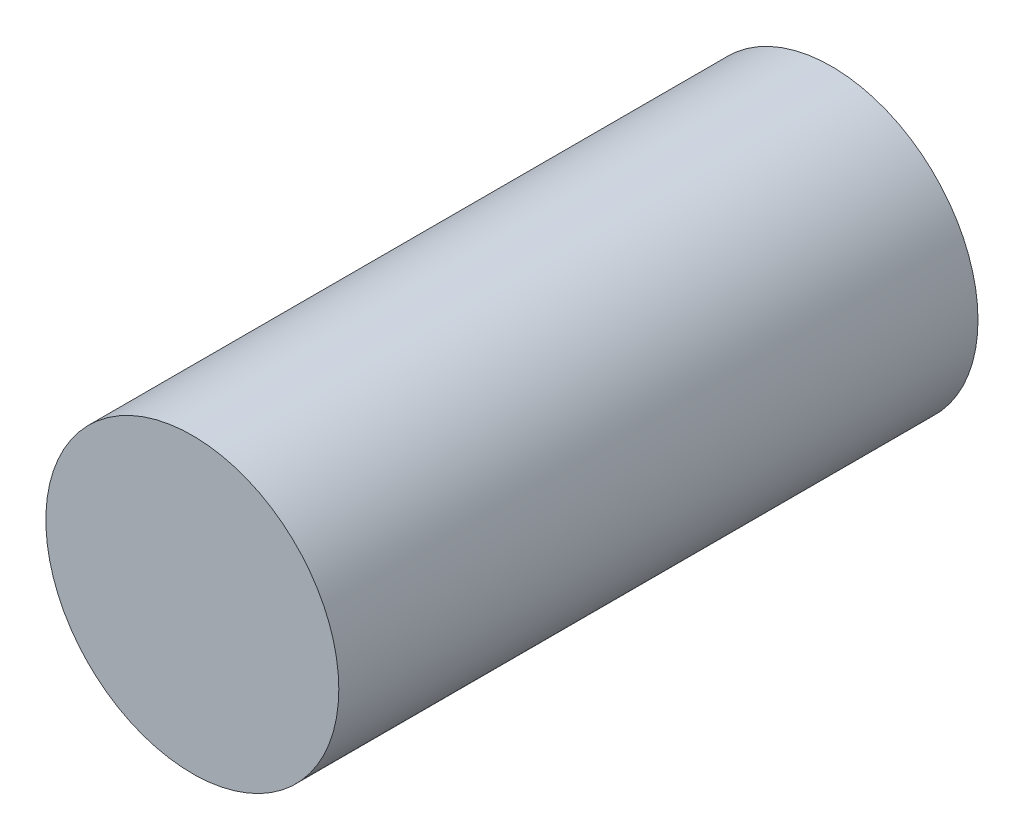
SolidWorks part; units mm, degrees
ref_plane "Plan de face" through (0, 0, 0) normal (0, 0, 1) x (1, 0, 0)
ref_plane "Plan de dessus" through (0, 0, 0) normal (0, 1, 0) x (1, 0, 0)
ref_plane "Plan de droite" through (0, 0, 0) normal (1, 0, 0) x (0, 0, -1)
sketch "Esquisse1" plane through (0, 0, 0) normal (0, 0, 1) x (1, 0, 0)
  circle A0 centre (0, 0) radius 5.5
  dimension "D1" = 11
extrude "Extrusion1" add sketch "Esquisse1" along normal blind 24
